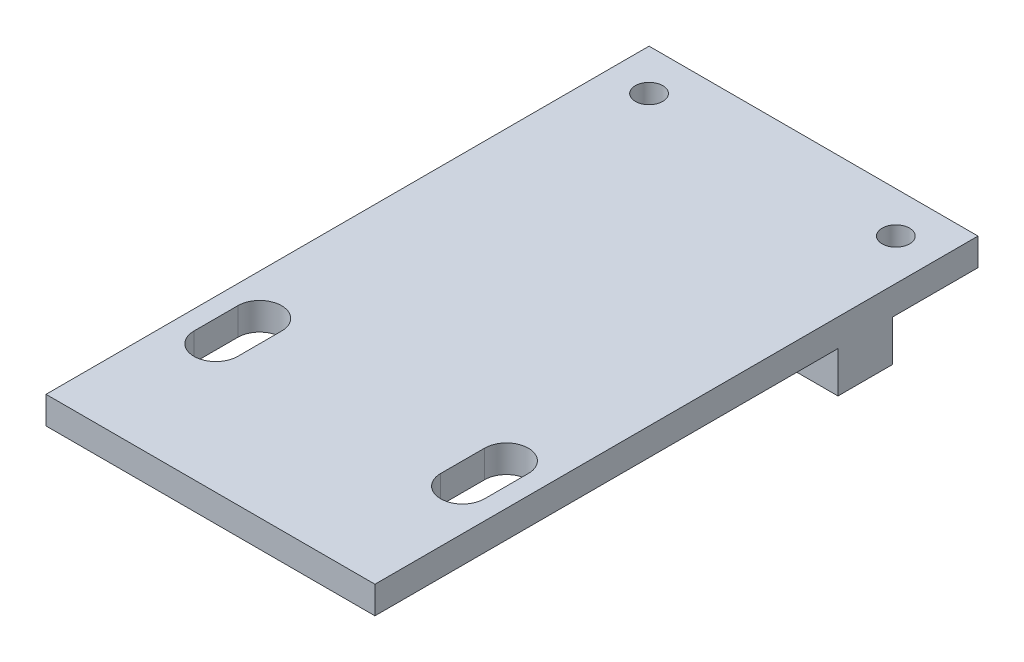
SolidWorks part; units mm, degrees
ref_plane "Front Plane" through (0, 0, 0) normal (0, 0, 1) x (1, 0, 0)
ref_plane "Top Plane" through (0, 0, 0) normal (0, 1, 0) x (1, 0, 0)
ref_plane "Right Plane" through (0, 0, 0) normal (1, 0, 0) x (0, 0, -1)
sketch "Sketch1" plane through (0, 0, 0) normal (0, 1, 0) x (1, 0, 0)
  line L1 (0, 0) -> (24, 0)
  line L2 (0, 0) -> (0, 48)
  line L3 (0, 48) -> (24, 48)
  line L4 (24, 0) -> (24, 48)
extrude "Boss-Extrude1" add sketch "Sketch1" along normal blind 2
sketch "Sketch2" plane through (0, 2, 0) normal (0, 1, 0) x (1, 0, 0)
  line L0 (0, 48) -> (2.9957, 48) construction
  line L1 (24, 48) -> (0, 48) construction
  line L2 (2.9957, 48) -> (2.9957, 45.0048) construction
  line L3 (2.9957, 45.0048) -> (2.9957, 48) construction
  line L4 (2.9957, 48) -> (24, 48) construction
  line L5 (24, 48) -> (21.0005, 48) construction
  line L6 (21.0005, 48) -> (21.0005, 45.0048) construction
  circle A0 centre (2.9957, 45.0048) radius 1
  circle A1 centre (21.0005, 45.0048) radius 1
extrude "Cut-Extrude1" cut sketch "Sketch2" against normal blind 2
sketch "Sketch3" plane through (0, 2, 0) normal (0, 1, 0) x (1, 0, 0)
  line L0 (0, 0) -> (0, 17.9951) construction
  line L1 (0, 48) -> (0, 0) construction
  line L2 (0, 17.9951) -> (24, 17.9951) construction
  line L3 (24, 0) -> (24, 48) construction
  line L4 (0, 17.9951) -> (2.9972, 17.9951) construction
  line L5 (2.9972, 17.9951) -> (2.9972, 14.9951) construction
  line L6 (2.9972, 14.9951) -> (24, 14.9951) construction
  line L7 (24, 14.9951) -> (21, 14.9951) construction
  line L8 (1.3972, 16.5951) -> (1.3972, 13.3951)
  line L9 (4.5972, 16.5951) -> (4.5972, 13.3951)
  line L10 (4.5972, 13.3951) -> (19.4, 16.5951)
  line L11 (19.4, 16.5951) -> (19.4, 13.3951)
  line L12 (22.6, 16.5951) -> (22.6, 13.3951)
  circle A0 centre (2.9972, 14.9951) radius 1.6
  circle A1 centre (21, 14.9951) radius 1.6
  circle A2 centre (2.9972, 16.5951) radius 1.6
  circle A3 centre (21, 16.5951) radius 1.6
  circle A4 centre (21, 13.3951) radius 1.6
  circle A5 centre (2.9972, 13.3951) radius 1.6
extrude "Cut-Extrude2" cut sketch "Sketch3" against normal blind 2 contours A0 A2 | A0 A2 | A0 A5 | A5 A0 | A5 A0 A2 | A5 A2 A0 | A2 L8 A0 | A5 A0 L8 | A5 L9 A0 | A2 A0 L9 | A1 A3 | A1 A3 | A1 A4 | A4 A1 | A4 A1 A3 | A4 L12 A1 | A3 A1 L12 | A4 A3 A1 | A3 L11 A1 | A4 A1 L11
sketch "Sketch5" plane through (0, 0, 0) normal (0, -1, 0) x (-1, 0, 0)
  line L0 (-12, 48) -> (-12, 40.0992) construction
  line L1 (-24, 48) -> (0, 48) construction
  line L2 (-12, 40.0992) -> (-12, 19.1072) construction
  line L3 (-12, 19.1072) -> (-9.9967, 19.1072) construction
  line L4 (-9.9967, 19.1072) -> (-13.9994, 19.1072) construction
  line L6 (-9.9967, 19.1072) -> (-13.9994, 19.1072)
  line L7 (-9.9967, 19.1072) -> (-9.9967, 48)
  line L8 (-9.9967, 48) -> (-13.9994, 48)
  line L9 (-13.9994, 19.1072) -> (-13.9994, 48)
extrude "Boss-Extrude2" add sketch "Sketch5" along normal blind 3
sketch "Sketch7" plane through (0, -3, 0) normal (0, -1, 0) x (-1, 0, 0)
  line L0 (-9.9967, 19.1072) -> (-9.9967, 48) construction
  line L1 (-13.9994, 48) -> (-9.9967, 48)
  line L2 (-13.9994, 48) -> (-13.9994, 41.7785)
  line L3 (-13.9994, 41.7785) -> (-9.9967, 41.7785)
  line L4 (-9.9967, 48) -> (-9.9967, 41.7785)
extrude "Cut-Extrude3" cut sketch "Sketch7" against normal up to surface (3 mm away) up to face at (13.2489, 0, -28.7768)
sketch "Sketch8" plane through (0, 0, 0) normal (0, -1, 0) x (-1, 0, 0)
  line L0 (-24, 0) -> (-24, 48) construction
  line L1 (-13.9994, 41.7785) -> (-24, 41.7785)
  line L2 (-13.9994, 41.7785) -> (-13.9994, 37.7833)
  line L3 (-13.9994, 37.7833) -> (-24, 37.7833)
  line L4 (-24, 41.7785) -> (-24, 37.7833)
  line L5 (0, 48) -> (0, 0) construction
  line L6 (-9.9967, 41.7785) -> (0, 41.7785)
  line L7 (-9.9967, 41.7785) -> (-9.9967, 37.7833)
  line L8 (-9.9967, 37.7833) -> (0, 37.7833)
  line L9 (0, 41.7785) -> (0, 37.7833)
extrude "Boss-Extrude3" add sketch "Sketch8" along normal blind 3
sketch "Sketch9" plane through (0, 0, 0) normal (0, 0, 1) x (1, 0, 0)
  line L1 (24, 0) -> (0, 0)
  line L2 (24, 0) -> (24, 2)
  line L3 (24, 2) -> (0, 2)
  line L4 (0, 0) -> (0, 2)
extrude "Cut-Extrude4" cut sketch "Sketch9" against normal blind 4
